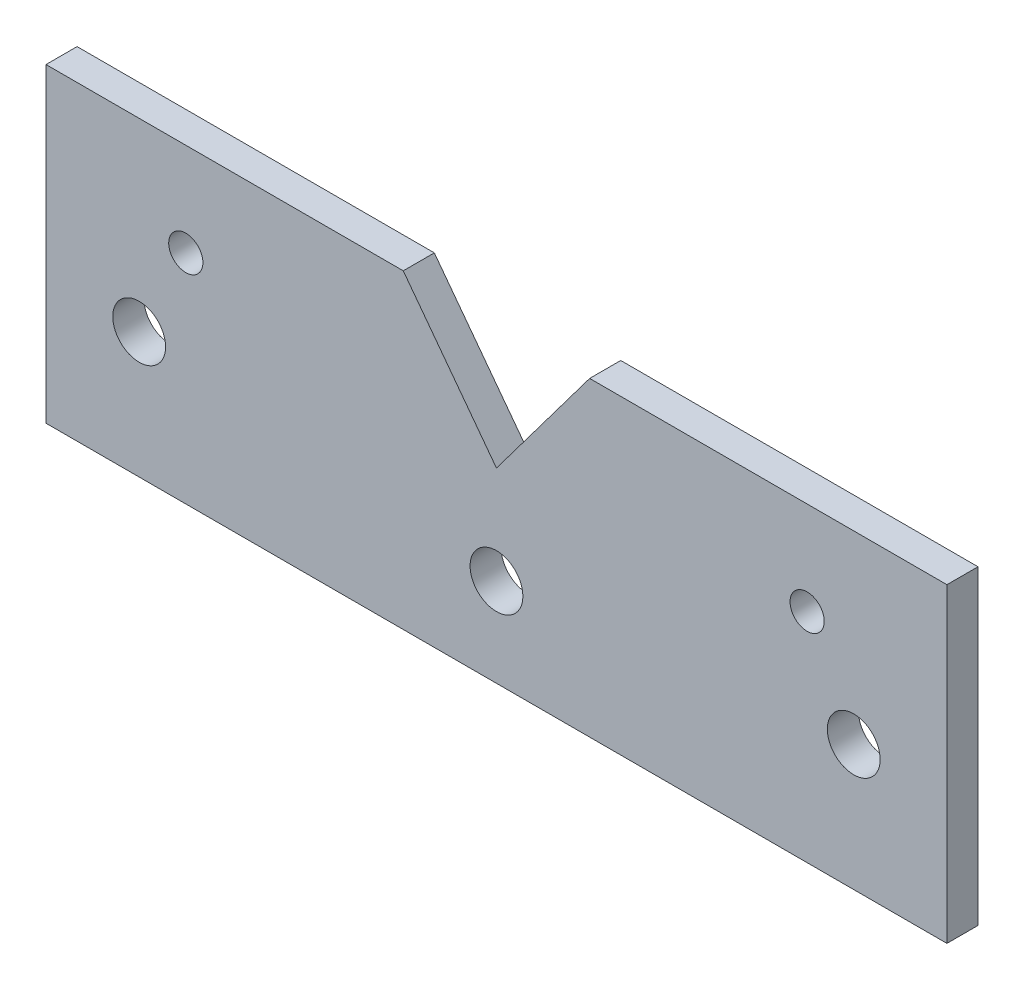
SolidWorks part; units mm, degrees
ref_plane "Front Plane" through (0, 0, 0) normal (0, 0, 1) x (1, 0, 0)
ref_plane "Top Plane" through (0, 0, 0) normal (0, 1, 0) x (1, 0, 0)
ref_plane "Right Plane" through (0, 0, 0) normal (1, 0, 0) x (0, 0, -1)
sketch "Sketch1" plane through (0, 0, 0) normal (0, 0, 1) x (1, 0, 0)
  line L0 (0, 0) -> (0, 50)
  line L1 (0, 50) -> (57.5, 50)
  line L2 (57.5, 50) -> (72.5, 30)
  line L3 (72.5, 30) -> (87.5, 50)
  line L4 (87.5, 50) -> (145, 50)
  line L5 (145, 50) -> (145, 0)
  line L6 (145, 0) -> (0, 0)
  line L7 (72.5, 30) -> (72.5, 0) construction
  line L8 (0, 14.25) -> (145, 14.25) construction
  line L9 (0, 20.25) -> (145, 20.25) construction
  circle A2 centre (15, 20.25) radius 4.25
  circle A3 centre (130, 20.25) radius 4.25
  circle A4 centre (72.5, 14.25) radius 4.25
  circle A5 centre (22.5, 35) radius 2.75
  circle A6 centre (122.5, 35) radius 2.75
  point P3 (72.5, 0)
  dimension "D12" = 8.5
  dimension "D13" = 8.5
  dimension "D14" = 8.5
  dimension "D16" = 5.5
  dimension "D17" = 5.5
  dimension "D1" = 50
  dimension "D2" = 145
  dimension "D3" = 20
  dimension "D4" = 30
  dimension "D5" = 57.5
  dimension "D6" = 57.5
  dimension "D7" = 14.25
  dimension "D8" = 20.25
  dimension "D9" = 50
  dimension "D10" = 50
  dimension "D11" = 35
  dimension "D15" = 35
extrude "Boss-Extrude1" add sketch "Sketch1" along normal blind 5
equation "\"SyringeDiameter\"= 20"
equation "\"SyringeLength\"= 100"
equation "\"PlungerDiameter\"= 5"
equation "\"PlungerLength\"= 110"
equation "\"VSlotWidth\"= 30"
equation "\"VSlotDepth\"= 20"
equation "\"FingerFlangeDiameter\"= 30"
equation "\"VSlotBackPlateThickness\"= 5"
equation "\"GuideRodDiameter\"= 8.5"
equation "\"LeadScrewDiameter\"= 8.5"
equation "\"GuideRodSpacing\"= 16.25 + 4"
equation "\"LeadScrewSpacing\"= 10.25 + 4"
equation "\"ThreadedInsertDiameter\"= 7.1"
equation "\"ThreadedInsertDepth\"= 10"
equation "\"MountingHoleDiameter\"= 3"
equation "\"MountingHoleSpacing\"= 20"
equation "\"BlockHeight\"= 50"
equation "\"BlockWidth\"= \"RodToScrew\" * 2 + 30"
equation "\"BlockDepth\"= 20"
equation "\"VSlotAngle\"= 90"
equation "\"GuideRodSideWidth\"= 10"
equation "\"ScrewHeight\"= 35"
equation "\"ThreadedInsertSideWidth\"= 50"
equation "\"D1@Sketch1\"=\"BlockHeight\""
equation "\"D2@Sketch1\"=\"BlockWidth\""
equation "\"D3@Sketch1\"=\"VSlotDepth\""
equation "\"D4@Sketch1\"=\"VSlotWidth\""
equation "\"D12@Sketch1\"=\"GuideRodDiameter\""
equation "\"D13@Sketch1\"=\"GuideRodDiameter\""
equation "\"D14@Sketch1\"=\"LeadScrewDiameter\""
equation "\"ScrewWidth\"= 5.5"
equation "\"D1@Boss-Extrude1\"=\"VSlotBackPlateThickness\""
equation "\"ScrewMountDistance\"= 25"
equation "\"RodtoRod\"= 115"
equation "\"RodToScrew\"= \"RodtoRod\" / 2"
equation "\"D5@Sketch1\"=\"RodToScrew\""
equation "\"D6@Sketch1\"=\"RodToScrew\""
equation "\"D7@Sketch1\"=\"LeadScrewSpacing\""
equation "\"D8@Sketch1\"=\"GuideRodSpacing\""
equation "\"D9@Sketch1\"=\"ThreadedInsertSideWidth\""
equation "\"D10@Sketch1\"=\"ThreadedInsertSideWidth\""
equation "\"D11@Sketch1\"=\"ScrewHeight\""
equation "\"D15@Sketch1\"=\"ScrewHeight\""
equation "\"D16@Sketch1\"=\"ScrewWidth\""
equation "\"D17@Sketch1\"=\"ScrewWidth\""
